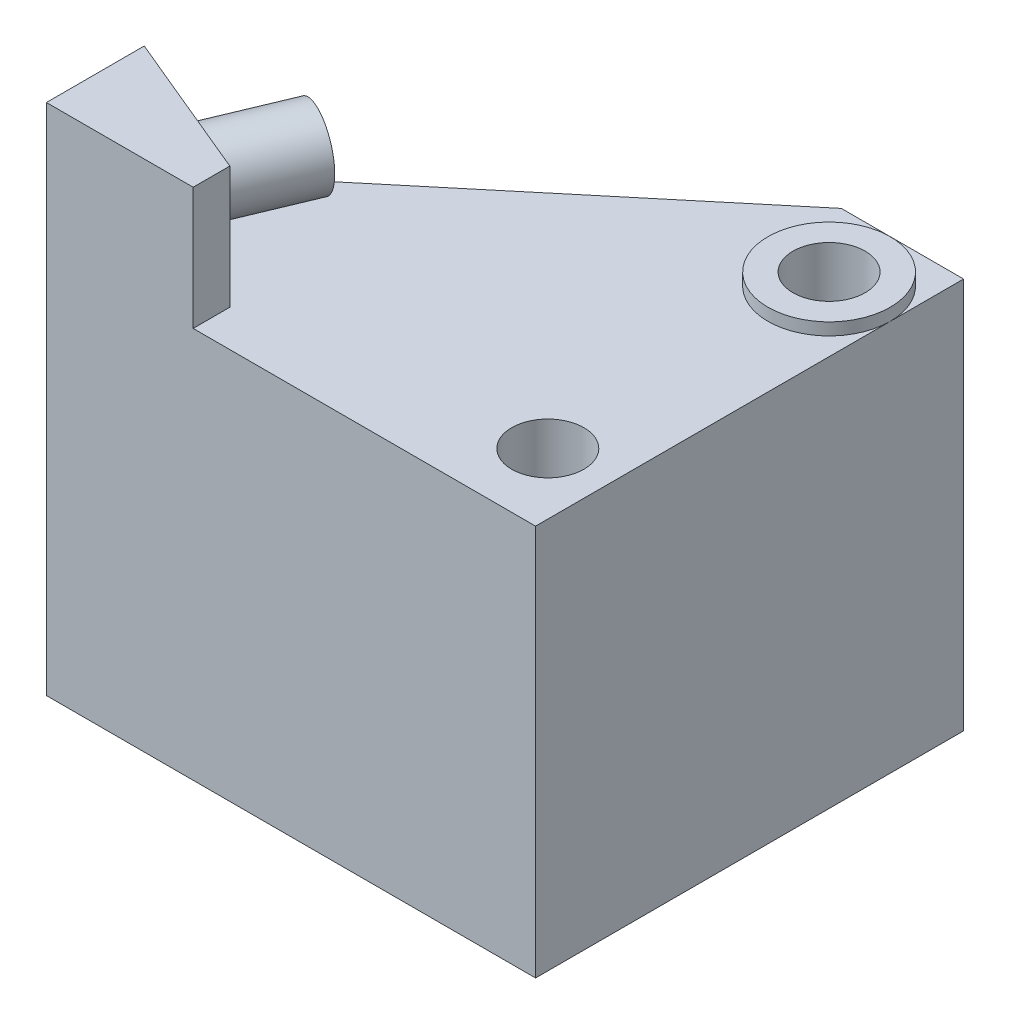
SolidWorks part; units mm, degrees
ref_plane "Спереди" through (0, 0, 0) normal (0, 0, 1) x (1, 0, 0)
ref_plane "Сверху" through (0, 0, 0) normal (0, 1, 0) x (1, 0, 0)
ref_plane "Справа" through (0, 0, 0) normal (1, 0, 0) x (0, 0, -1)
sketch "Эскиз2" plane through (0, 0, 0) normal (0, 1, 0) x (1, 0, 0)
  line L0 (-20, 5) -> (-5, 17.5)
  line L5 (-5, 17.5) -> (0, 17.5)
  line L6 (0, 17.5) -> (0, 0)
  line L7 (0, 0) -> (-20, 0)
  line L8 (-20, 0) -> (-20, 5)
  point P2 (0, 0)
  point P7 (-5.7457, 33.4326)
  point P9 (-24.6644, 5)
  dimension "D1" = 5
  dimension "D2" = 17.5
  dimension "D3" = 20
extrude "Бобышка-Вытянуть1" add sketch "Эскиз2" along normal blind 16
sketch "Эскиз3" plane through (0, 16, 0) normal (0, 1, 0) x (1, 0, 0)
  line L0 (-2.5, -975) -> (-2.5, 49025) construction
  line L1 (0, 17.5) -> (-5, 17.5) construction
  line L2 (-20, 0) -> (0, 0) construction
  circle A0 centre (-2.5, 14.5) radius 1.475
  circle A1 centre (-2.5, 3) radius 1.475
  point P5 (-2.5, 17.5)
  dimension "D1" = 2.95
  dimension "D2" = 3
  dimension "D3" = 3
extrude "Вырез-Вытянуть1" cut sketch "Эскиз3" against normal through all
sketch "Эскиз4" plane through (0, 16, 0) normal (0, 1, 0) x (1, 0, 0)
  line L0 (-20, 4) -> (-20, 0)
  line L1 (-20, 0) -> (-14, 0)
  line L2 (-20, 0) -> (0, 0) construction
  line L4 (-14, 0) -> (-14, 1.5)
  line L5 (-14, 1.5) -> (-20, 4)
  dimension "D1" = 4
  dimension "D2" = 6
  dimension "D3" = 1.5
extrude "Бобышка-Вытянуть2" add sketch "Эскиз4" along normal blind 5
sketch "Эскиз5" plane through (0, 16, 0) normal (0, 1, 0) x (1, 0, 0)
  line L0 (0, 0) -> (0, 17.5) construction
  circle A0 centre (-2.5, 14.5) radius 2.5
  circle A1 centre (-2.5, 14.5) radius 1.475
  circle A2 centre (-2.5, 14.5) radius 1.475 construction
extrude "Бобышка-Вытянуть3" add sketch "Эскиз5" along normal blind 0.5
sketch "Эскиз6" plane through (-1.5385, 0, 3.6923) normal (0.3846, 0, -0.9231) x (-0.9231, 0, -0.3846)
  line L0 (16.75, -979) -> (16.75, 49021) construction
  line L2 (13.5, 21) -> (20, 21) construction
  line L4 (-980.3226, 18.5) -> (49019.6774, 18.5) construction
  line L5 (20, 21) -> (20, 16) construction
  circle A0 centre (16.75, 18.5) radius 1.5
  point P5 (16.75, 21)
  point P7 (16.3233, 18.5)
  point P13 (20, 18.5)
  dimension "D1" = 3
extrude "Бобышка-Вытянуть4" add sketch "Эскиз6" along normal blind 4
